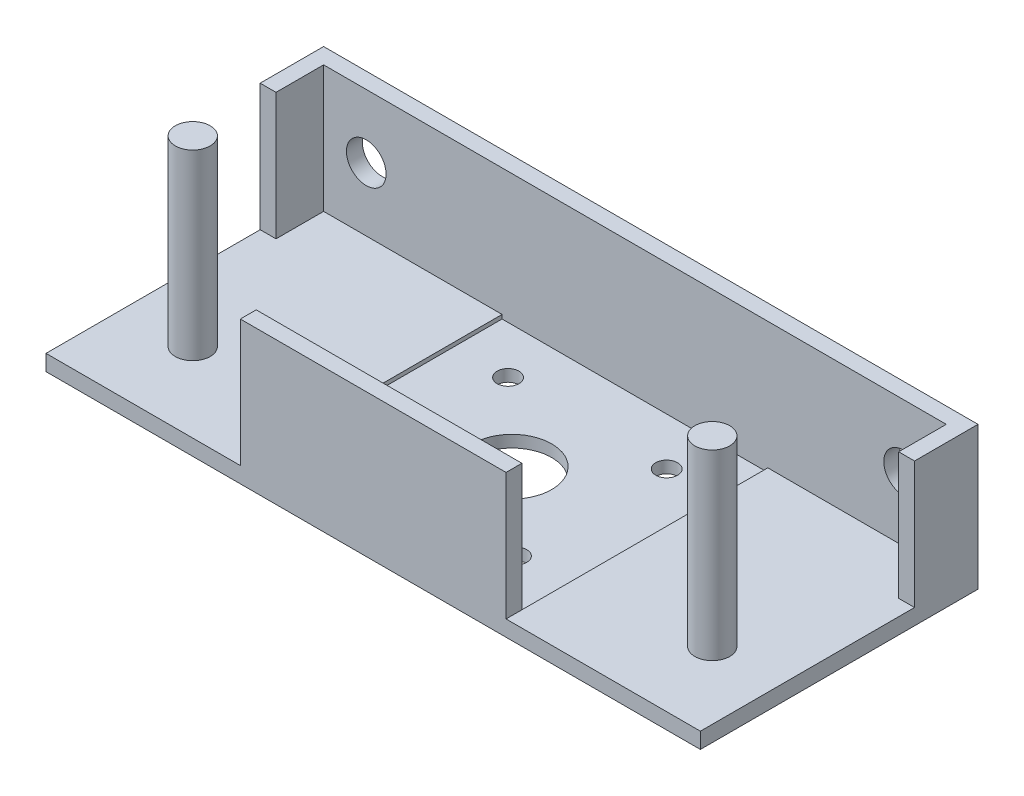
SolidWorks part; units mm, degrees
ref_plane "Front Plane" through (0, 0, 0) normal (0, 0, 1) x (1, 0, 0)
ref_plane "Top Plane" through (0, 0, 0) normal (0, 1, 0) x (1, 0, 0)
ref_plane "Right Plane" through (0, 0, 0) normal (1, 0, 0) x (0, 0, -1)
sketch "Sketch1" plane through (0, 0, 0) normal (0, 1, 0) x (1, 0, 0)
  line L0 (0, 0) -> (0, -14.43) construction
  line L1 (-37.5, 20) -> (37.5, 20)
  line L2 (-37.5, 20) -> (-37.5, -20)
  line L3 (-37.5, -20) -> (37.5, -20)
  line L4 (37.5, 20) -> (37.5, -20)
  line L5 (-37.5, 20) -> (37.5, -20) construction
  line L6 (-37.5, -20) -> (37.5, 20) construction
  line L7 (0, 0) -> (6.508, 0) construction
  line L8 (-5, 10) -> (5, 10)
  line L9 (-5, 10) -> (-5, -10)
  line L10 (-5, -10) -> (5, -10)
  line L11 (5, 10) -> (5, -10)
  line L12 (-5, 10) -> (5, -10) construction
  line L13 (-5, -10) -> (5, 10) construction
  circle A0 centre (-21, 0) radius 5
  circle A1 centre (-30, 8.25) radius 1.7
  circle A2 centre (-12, 8.25) radius 1.7
  circle A3 centre (-12, -8.25) radius 1.7
  circle A4 centre (-30, -8.25) radius 1.7
  circle A5 centre (12, 8.25) radius 1.7
  circle A6 centre (12, -8.25) radius 1.7
  circle A7 centre (21, 0) radius 5
  circle A8 centre (30, -8.25) radius 1.7
  circle A9 centre (30, 8.25) radius 1.7
  point P0 (0, 0)
  dimension "D3" = 10
  dimension "D4" = 16.5
  dimension "D5" = 16.5
  dimension "D6" = 18
  dimension "D9" = 10
  dimension "D11" = 20
  dimension "D13" = 7.5
  dimension "D17" = 3.4
  dimension "D19" = 11.75
  dimension "D20" = 11.75
  dimension "D1" = 75
  dimension "D2" = 40
  dimension "D10" = 10
  dimension "D7" = 2
  dimension "D8" = 2
extrude "Boss-Extrude1" add sketch "Sketch1" along normal blind 3
sketch "Sketch2" plane through (0, 3, 0) normal (0, 1, 0) x (1, 0, 0)
  line L0 (-37.5, 20) -> (-37.5, -20) construction
  line L1 (-33.5, 14) -> (33.5, 14)
  line L2 (-33.5, 14) -> (-33.5, -14)
  line L3 (-33.5, -14) -> (33.5, -14)
  line L4 (33.5, 14) -> (33.5, -14)
  line L5 (37.5, -20) -> (37.5, 20) construction
  line L6 (37.5, 20) -> (-37.5, 20) construction
  line L7 (-37.5, -20) -> (37.5, -20) construction
  dimension "D1" = 4
  dimension "D2" = 4
  dimension "D3" = 6
  dimension "D4" = 6
extrude "Cut-Extrude1" cut sketch "Sketch2" against normal through all both and the other way through all
sketch "Sketch3" plane through (0, 3, 0) normal (0, 1, 0) x (1, 0, 0)
  line L1 (37.5, 20) -> (-37.5, 20)
  line L2 (37.5, 20) -> (37.5, 35)
  line L3 (37.5, 35) -> (-37.5, 35)
  line L4 (-37.5, 20) -> (-37.5, 35)
  line L5 (-37.5, -20) -> (37.5, -20)
  line L6 (-37.5, -20) -> (-37.5, -35)
  line L7 (-37.5, -35) -> (37.5, -35)
  line L8 (37.5, -20) -> (37.5, -35)
  line L10 (-37.5, 20) -> (-33.5, 20)
  line L11 (-37.5, 20) -> (-37.5, -20)
  line L12 (-37.5, -20) -> (-33.5, -20)
  line L13 (-33.5, 20) -> (-33.5, -20)
  line L14 (37.5, 20) -> (33.5, 20)
  line L15 (37.5, 20) -> (37.5, -20)
  line L16 (37.5, -20) -> (33.5, -20)
  line L17 (33.5, 20) -> (33.5, -20)
  line M3 (-33.5, -14) -> (-33.5, 14)
  line M5 (33.5, 14) -> (33.5, -14)
  line M11 (37.5, -20) -> (37.5, 20)
  line M12 (37.5, 20) -> (-37.5, 20)
  line M13 (-37.5, 20) -> (-37.5, -20)
  line M14 (-37.5, -20) -> (37.5, -20)
  dimension "D1" = 15
  dimension "D2" = 15
extrude "Boss-Extrude3" add sketch "Sketch3" along normal blind 110 and the other way blind 3 contours L8 L5 L6 L7 M14 | L4 L1 L2 L3 M12 | L17 M12 M5 M14 M11 | L13 L1 M13 M14 M3
sketch "Sketch6" plane through (0, 3, 0) normal (0, 1, 0) x (1, 0, 0)
  line L0 (-37.5, -35) -> (37.5, -35) construction
  line L1 (-33.5, -20) -> (33.5, -20)
  line L2 (-33.5, -20) -> (-33.5, -31)
  line L3 (-33.5, -31) -> (33.5, -31)
  line L4 (33.5, -20) -> (33.5, -31)
  line L5 (33.5, 20) -> (-33.5, 20)
  line L6 (33.5, 20) -> (33.5, 31)
  line L7 (33.5, 31) -> (-33.5, 31)
  line L8 (-33.5, 20) -> (-33.5, 31)
  line L9 (37.5, 35) -> (-37.5, 35) construction
  dimension "D1" = 4
  dimension "D2" = 4
extrude "Cut-Extrude4" cut sketch "Sketch6" along normal through all
sketch "Sketch7" plane through (-37.5, 0, 0) normal (-1, 0, 0) x (0, 0, 1)
  line L0 (35, 0) -> (35, 113) construction
  line L1 (-35, 113) -> (35, 113)
  line L2 (-35, 113) -> (-35, 76)
  line L3 (-35, 76) -> (35, 76)
  line L4 (35, 113) -> (35, 76)
  dimension "D1" = 37
extrude "Boss-Extrude4" add sketch "Sketch7" along normal blind 45
ref_plane "Plane1" through (0, 0, 0) normal (1, 0, 0) x (0, 0, -1)
mirror "Mirror2" about plane through (0, 0, 0) normal (1, 0, 0) of "Boss-Extrude4"
sketch "Sketch8" plane through (0, 113, 0) normal (0, 1, 0) x (1, 0, 0)
  line L0 (-82.5, -35) -> (-82.5, 35) construction
  line L1 (-33.5, 31) -> (-78.5, 31)
  line L2 (-33.5, 31) -> (-33.5, -31)
  line L3 (-33.5, -31) -> (-78.5, -31)
  line L4 (-78.5, 31) -> (-78.5, -31)
  line L5 (33.5, -31) -> (78.5, -31)
  line L6 (33.5, -31) -> (33.5, 31)
  line L7 (33.5, 31) -> (78.5, 31)
  line L8 (78.5, -31) -> (78.5, 31)
  line L9 (82.5, -35) -> (82.5, 35) construction
  dimension "D1" = 4
  dimension "D2" = 4
extrude "Cut-Extrude6" cut sketch "Sketch8" against normal blind 29
sketch "Sketch9" plane through (-82.5, 0, 0) normal (-1, 0, 0) x (0, 0, 1)
  line L18 (-31, 84) -> (31, 84) construction
  line L19 (-19, 84) -> (19, 84)
  line L20 (-19, 84) -> (-19, 112.5)
  line L21 (-19, 112.5) -> (19, 112.5)
  line L22 (19, 84) -> (19, 112.5)
  line L25 (-31, 84) -> (-31, 113) construction
  dimension "D1" = 38
  dimension "D2" = 12
  dimension "D3" = 28.5
sketch "Sketch11" plane through (0, 0, 35) normal (0, 0, 1) x (1, 0, 0)
  line L0 (82.5, 76) -> (82.5, 113) construction
  line L1 (-82.5, 76) -> (-37.5, 76)
  line L2 (-82.5, 76) -> (-82.5, 80)
  line L3 (-82.5, 80) -> (-37.5, 80)
  line L4 (-37.5, 76) -> (-37.5, 80)
  line L5 (37.5, 76) -> (82.5, 76)
  line L6 (37.5, 76) -> (37.5, 80)
  line L7 (37.5, 80) -> (82.5, 80)
  line L8 (82.5, 76) -> (82.5, 80)
  line L11 (-78.5, 84) -> (-33.5, 84) construction
  line L12 (33.5, 84) -> (78.5, 84) construction
  dimension "D1" = 4
  dimension "D2" = 4
extrude "Cut-Extrude9" cut sketch "Sketch11" against normal through all
extrude "Cut-Extrude10" cut sketch "Sketch9" against normal through all
sketch "Sketch13" plane through (0, 84, 0) normal (0, 1, 0) x (1, 0, 0)
  line L0 (-78.5, 31) -> (-78.5, -31) construction
  line L1 (-57, 19) -> (-52, 19)
  line L2 (-57, 19) -> (-57, -19)
  line L3 (-57, -19) -> (-52, -19)
  line L4 (-52, 19) -> (-52, -19)
  line L7 (78.5, 31) -> (-78.5, 31) construction
  line L13 (-57, -19) -> (-57, 19)
  line L17 (-82.5, -19) -> (-107.5, -19)
  line L18 (-82.5, -19) -> (-82.5, 19)
  line L19 (-82.5, 19) -> (-107.5, 19)
  line L20 (-107.5, -19) -> (-107.5, 19)
  line L21 (-107.5, 19) -> (-61, 19)
  line L22 (-107.5, 19) -> (-107.5, -19)
  line L23 (-107.5, -19) -> (-61, -19)
  line L24 (-61, 19) -> (-61, -19)
  dimension "D1" = 21.5
  dimension "D2" = 5
  dimension "D3" = 38
  dimension "D4" = 12
  dimension "D5" = 25
  dimension "D6" = 46.5
extrude "Boss-Extrude5" add sketch "Sketch13" along normal blind 32 contours L4 L1 L2 L3
sketch "Sketch14" plane through (-57, 0, 0) normal (-1, 0, 0) x (0, 0, 1)
  line L0 (-19, 116) -> (-19, 84) construction
  line L4 (19, 112.5) -> (-19, 112.5) construction
  circle A0 centre (0, 98.25) radius 5
  circle A1 centre (-9, 106.5) radius 1.7
  circle A2 centre (9, 106.5) radius 1.7
  circle A3 centre (9, 90) radius 1.7
  circle A4 centre (-9, 90) radius 1.7
  dimension "D1" = 19
  dimension "D2" = 9
  dimension "D3" = 10
  dimension "D6" = 3.4
  dimension "D7" = 14.25
  dimension "D8" = 16.5
  dimension "D9" = 18
  dimension "D10" = 8.25
  dimension "D4" = 2
  dimension "D5" = 2
extrude "Cut-Extrude11" cut sketch "Sketch14" against normal blind 32
mirror "Mirror4" about plane through (0, 0, 0) normal (1, 0, 0) of "Boss-Extrude5", "Cut-Extrude11"
sketch "Sketch15" plane through (0, 113, 0) normal (0, 1, 0) x (1, 0, 0)
  line L1 (-82.5, 35) -> (82.5, 35)
  line L2 (-82.5, 35) -> (-82.5, -35)
  line L3 (-82.5, -35) -> (82.5, -35)
  line L4 (82.5, 35) -> (82.5, -35)
  line L5 (-78.5, 31) -> (78.5, 31)
  line L6 (-78.5, 31) -> (-78.5, -31)
  line L7 (-78.5, -31) -> (78.5, -31)
  line L8 (78.5, 31) -> (78.5, -31)
extrude "Boss-Extrude6" add sketch "Sketch15" along normal blind 3
sketch "Sketch16" plane through (0, 0, 35) normal (0, 0, 1) x (1, 0, 0)
  line L1 (-10, 14.0464) -> (10, 14.0464)
  line L2 (-10, 14.0464) -> (-10, 9.2258)
  line L3 (-10, 9.2258) -> (10, 9.2258)
  line L4 (10, 14.0464) -> (10, 9.2258)
  line L5 (-37.5, 0) -> (-37.5, 80) construction
  dimension "D1" = 20
  dimension "D2" = 27.5
extrude "Cut-Extrude12" cut sketch "Sketch16" against normal through all
sketch "Sketch18" plane through (0, 0, 35) normal (0, 0, 1) x (1, 0, 0)
  line L0 (57, 116) -> (57, 84) construction
  line L2 (33.5, 84) -> (78.5, 84) construction
  circle A0 centre (67.75, 100) radius 5
  dimension "D1" = 10.75
  dimension "D2" = 16
  dimension "D3" = 10
extrude "Cut-Extrude14" cut sketch "Sketch18" against normal through all
mirror "Mirror5" about plane through (0, 0, 0) normal (1, 0, 0) of "Cut-Extrude14"
mirror "Mirror6" about plane through (0, 116, 0) normal (0, 1, 0) of "Mirror4", "Boss-Extrude5", "Cut-Extrude11"
sketch "Sketch19" plane through (82.5, 0, 0) normal (1, 0, 0) x (0, 0, -1)
  line L0 (19, 148) -> (19, 84) construction
  line L1 (-19, 112.5) -> (19, 112.5)
  line L2 (-19, 112.5) -> (-19, 116)
  line L3 (-19, 116) -> (19, 116)
  line L4 (19, 112.5) -> (19, 116)
extrude "Cut-Extrude15" cut sketch "Sketch19" against normal blind 10
mirror "Mirror7" about plane through (0, 0, 0) normal (1, 0, 0) of "Cut-Extrude15"
sketch "Sketch20" plane through (0, 3, 0) normal (0, 1, 0) x (1, 0, 0)
  line L0 (33.5, 31) -> (-33.5, 31) construction
  line L1 (-5, -10) -> (5, -10)
  line L2 (-5, -10) -> (-5, 10)
  line L3 (-5, 10) -> (5, 10)
  line L4 (5, -10) -> (5, 10)
  line L5 (-5, -10) -> (5, 10) construction
  line L6 (-5, 10) -> (5, -10) construction
  line L7 (0, 0) -> (0, 17.5) construction
  line L8 (-37.5, 20) -> (37.5, 20)
  line L9 (-37.5, 20) -> (-37.5, -20)
  line L10 (-37.5, -20) -> (37.5, -20)
  line L11 (37.5, 20) -> (37.5, -20)
  line L12 (-37.5, 20) -> (37.5, -20) construction
  line L13 (-37.5, -20) -> (37.5, 20) construction
  line L14 (0, -34.1) -> (0, 34.1) construction
  circle A1 centre (-12, 17.5) radius 1.2
  circle A2 centre (-12, -17.5) radius 1.2
  circle A3 centre (-24, -17.5) radius 1.2
  circle A4 centre (-24, 17.5) radius 1.2
  circle A5 centre (12, -17.5) radius 1.2
  circle A6 centre (24, -17.5) radius 1.2
  circle A7 centre (12, 17.5) radius 1.2
  circle A8 centre (24, 17.5) radius 1.2
  point P2 (0, 0)
  point P10 (0, 0)
  dimension "D1" = 7
  dimension "D2" = 10
  dimension "D4" = 2.5
  dimension "D7" = 35
  dimension "D8" = 7
  dimension "D9" = 2.4
  dimension "D11" = 12
  dimension "D3" = 21
  dimension "D5" = 75
  dimension "D6" = 40
  dimension "D10" = 2
extrude "Cut-Extrude16" cut sketch "Sketch20" against normal blind 10 contours A4 | A1 | A7 | A3 | A2 | A8 | A5 | A6
sketch "Sketch21" plane through (0, 0, 35) normal (0, 0, 1) x (1, 0, 0)
  line L0 (0, -34.1) -> (0, 34.1) construction
  line L1 (37.5, 0) -> (27.5, 0)
  line L2 (37.5, 0) -> (37.5, 80)
  line L3 (37.5, 80) -> (27.5, 80)
  line L4 (27.5, 0) -> (27.5, 80)
  line L5 (-27.5, 0) -> (-27.5, 80)
  line L6 (-37.5, 80) -> (-27.5, 80)
  line L7 (-37.5, 0) -> (-37.5, 80)
  line L8 (-37.5, 0) -> (-27.5, 0)
  dimension "D1" = 10
  dimension "D2" = 80
extrude "Cut-Extrude17" cut sketch "Sketch21" against normal through all
sketch "Sketch22" plane through (0, 0, 35) normal (0, 0, 1) x (1, 0, 0)
  line L1 (-27.5, 0) -> (27.5, 0)
  line L2 (-27.5, 0) -> (-27.5, 80)
  line L3 (-27.5, 80) -> (27.5, 80)
  line L4 (27.5, 0) -> (27.5, 80)
extrude "Cut-Extrude18" cut sketch "Sketch22" against normal through all
sketch "Sketch23" plane through (0, 80, 0) normal (0, -1, 0) x (1, 0, 0)
  line L1 (-33.5, 31) -> (33.5, 31)
  line L2 (-33.5, 31) -> (-33.5, -31)
  line L3 (-33.5, -31) -> (33.5, -31)
  line L4 (33.5, 31) -> (33.5, -31)
extrude "Boss-Extrude7" add sketch "Sketch23" against normal blind 3
sketch "Sketch24" plane through (0, 83, 0) normal (0, 1, 0) x (1, 0, 0)
  line L5 (78.5, 31) -> (-78.5, 31) construction
  line L9 (33.5, -31) -> (-33.5, -31) construction
  line L10 (0, 0) -> (0, 16.8876) construction
  line L11 (0, -34.1) -> (0, 34.1) construction
  circle A0 centre (0, 0) radius 10
  circle A1 centre (-20, 19) radius 2.75
  circle A2 centre (-20, -19) radius 2.75
  circle A3 centre (20, -19) radius 2.75
  circle A4 centre (20, 19) radius 2.75
  dimension "D1" = 20
  dimension "D2" = 12
  dimension "D3" = 20
  dimension "D4" = 12
extrude "Cut-Extrude19" cut sketch "Sketch24" against normal through all
sketch "Sketch25" plane through (57, 0, 0) normal (1, 0, 0) x (0, 0, -1)
  line L1 (-19, 148) -> (19, 148)
  line L2 (-19, 148) -> (-19, 84)
  line L3 (-19, 84) -> (19, 84)
  line L4 (19, 148) -> (19, 84)
extrude "Cut-Extrude20" cut sketch "Sketch25" against normal blind 115
sketch "Sketch26" plane through (0, 116, 0) normal (0, 1, 0) x (1, 0, 0)
  line L0 (33.5, 31) -> (33.5, -31) construction
  line L1 (82.5, -35) -> (33.5, -35)
  line L2 (82.5, -35) -> (82.5, 0)
  line L3 (82.5, 0) -> (33.5, 0)
  line L4 (33.5, -35) -> (33.5, 0)
extrude "Cut-Extrude21" cut sketch "Sketch26" against normal blind 32
mirror "Mirror8" about plane through (0, 0, 0) normal (1, 0, 0) of "Cut-Extrude21"
sketch "Sketch27" plane through (0, 84, 0) normal (0, 1, 0) x (1, 0, 0)
  line L0 (82.5, 19) -> (82.5, -35) construction
  line L1 (33.5, -35) -> (82.5, -35) construction
  circle A0 centre (65.5, -15) radius 4.4
  dimension "D1" = 8.8
  dimension "D2" = 17
  dimension "D3" = 20
extrude "Boss-Extrude8" add sketch "Sketch27" along normal blind 46
mirror "Mirror9" about plane through (0, 0, 0) normal (1, 0, 0) of "Boss-Extrude8"
